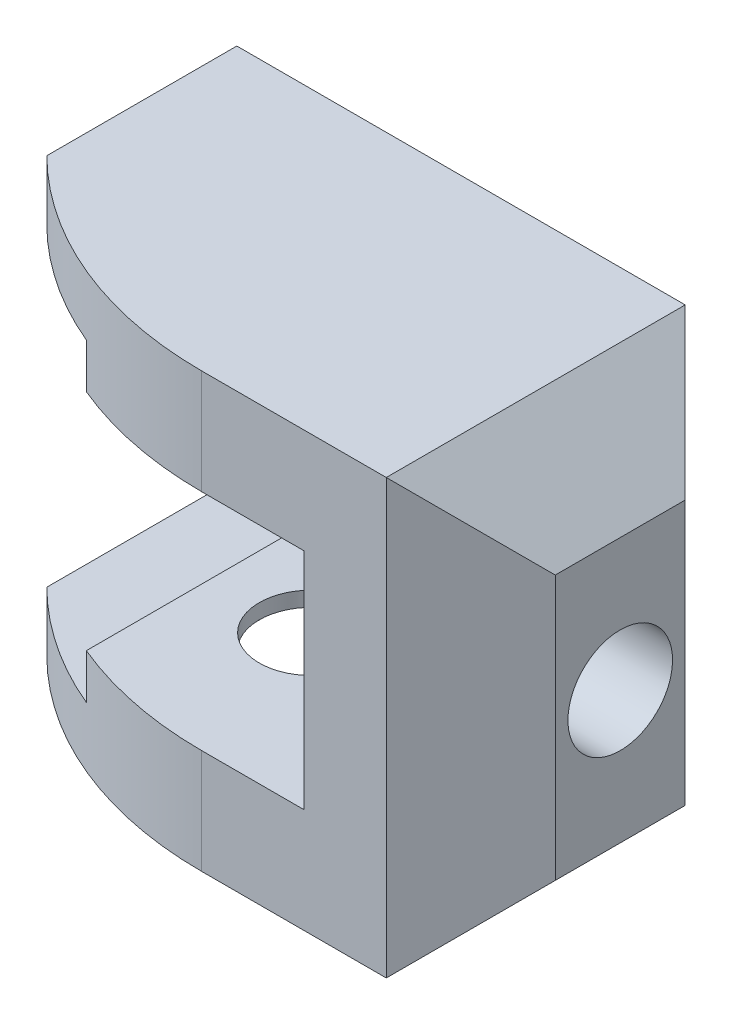
SolidWorks part; units mm, degrees
material "1060 Alloy"
ref_plane "Front Plane" through (0, 0, 0) normal (0, 0, 1) x (1, 0, 0)
ref_plane "Top Plane" through (0, 0, 0) normal (0, 1, 0) x (1, 0, 0)
ref_plane "Right Plane" through (0, 0, 0) normal (1, 0, 0) x (0, 0, -1)
sketch "Sketch2" plane through (0, 0, 0) normal (0, 0, 1) x (1, 0, 0)
  line L0 (60, 58) -> (71.3057, 46.6943)
  line L1 (0, 0) -> (60, 0)
  line L3 (0, 58) -> (60, 58)
  line L5 (71.3057, 46.6943) -> (71.3057, 11.3057)
  line L6 (71.3057, 11.3057) -> (60, 0)
  line L7 (0, 58) -> (0, 50)
  line L8 (0, 50) -> (16, 50)
  line L9 (16, 50) -> (16, 44)
  line L10 (16, 44) -> (45.9742, 44)
  line L11 (45.9742, 44) -> (49, 44)
  line L12 (49, 44) -> (49, 14)
  line L13 (49, 14) -> (16, 14)
  line L14 (16, 14) -> (16, 8)
  line L15 (16, 8) -> (0, 8)
  line L16 (0, 8) -> (0, 0)
  dimension "D1" = 45
  dimension "D2" = 45
  dimension "D3" = 8
  dimension "D4" = 6
  dimension "D5" = 8
  dimension "D6" = 6
  dimension "D7" = 16
  dimension "D8" = 16
  dimension "D9" = 11
  dimension "D10" = 11
  dimension "D11" = 58
  dimension "D12" = 60
extrude "Boss-Extrude1" add sketch "Sketch2" along normal blind 40
sketch "Sketch4" plane through (0, 0, 0) normal (0, -1, 0) x (1, 0, 0)
  line L0 (0, 40) -> (0, 0) construction
  line L1 (0, 40) -> (60, 40) construction
  line L2 (0, 25.4269) -> (0, 40)
  line L3 (0, 40) -> (35.2836, 40)
  arc A0 (0, 25.4269) -> (35.2836, 40) centre (35.2836, -10) cw
  dimension "D1" = 50
extrude "Cut-Extrude2" cut sketch "Sketch4" against normal through all
sketch "Sketch12" plane through (0, 0, 0) normal (0, 1, 0) x (1, 0, 0)
  line L0 (60, 0) -> (71.3057, -11.3057)
  line L1 (71.3057, 0) -> (60, 0) construction
  line L2 (60, -40) -> (60, 0) construction
  line L3 (71.3057, -40) -> (71.3057, 0) construction
  line L4 (71.3057, -11.3057) -> (71.3057, 0)
  line L5 (71.3057, 0) -> (60, 0)
  line L6 (60, -40) -> (71.3057, -28.6943)
  line L7 (71.3057, -28.6943) -> (71.3057, -40)
  line L8 (71.3057, -40) -> (60, -40)
  dimension "D1" = 45
  dimension "D2" = 45
extrude "Cut-Extrude3" cut sketch "Sketch12" along normal through all
sketch "Sketch14" plane through (71.3057, 0, 0) normal (1, 0, 0) x (0, 0, -1)
  circle A0 centre (-20, 29) radius 7
  dimension "D1" = 14
extrude "Cut-Extrude4" cut sketch "Sketch14" against normal through all
sketch "Sketch15" plane through (0, 0, 0) normal (0, -1, 0) x (1, 0, 0)
  circle A0 centre (29, 19) radius 7
  dimension "D1" = 14
extrude "Cut-Extrude5" cut sketch "Sketch15" against normal up to next
sketch "Sketch16" plane through (0, 44, 0) normal (0, -1, 0) x (1, 0, 0)
  circle A0 centre (29, 19) radius 7
extrude "Cut-Extrude6" cut sketch "Sketch16" against normal blind 2
sketch "Sketch21" plane through (0, 0, 0) normal (0, -1, 0) x (1, 0, 0)
  line L8 (0, 25.4269) -> (0, 0) construction
  line L9 (0, 22.5433) -> (0, 2)
  line L12 (58, 38) -> (35.2836, 38)
  line L13 (2, 24.5861) -> (2, 2)
  line L14 (2, 2) -> (58, 2)
  line L15 (58, 2) -> (58, 38)
  line L16 (58, 38) -> (35.2836, 38)
  line L18 (0, 2) -> (58, 2)
  line L19 (58, 2) -> (58, 38)
  arc A3 (35.2836, 38) -> (2, 24.5861) centre (35.2836, -10) ccw
  arc A4 (35.2836, 38) -> (0, 22.5433) centre (35.2836, -10) ccw
  dimension "D1" = 2
extrude "Cut-Extrude9" cut sketch "Sketch21" against normal blind 6
sketch "Sketch22" plane through (0, 6, 0) normal (0, -1, 0) x (1, 0, 0)
  line L0 (0, 2) -> (58, 2) construction
  line L1 (58, 2) -> (16.0233, 2)
  line L2 (58, 2) -> (58, 33.9663)
  line L3 (58, 33.9663) -> (16.0233, 33.9663)
  line L4 (16.0233, 2) -> (16.0233, 33.9663)
  arc A0 (35.2836, 38) -> (0, 22.5433) centre (35.2836, -10) ccw construction
extrude "Cut-Extrude11" cut sketch "Sketch22" against normal blind 6
sketch "Sketch23" plane through (0, 6, 0) normal (0, -1, 0) x (1, 0, 0)
  line L0 (16.0233, 33.9663) -> (58, 33.9663)
  line L1 (58, 33.9663) -> (58, 38)
  line L2 (58, 38) -> (34.0321, 37.9837)
  arc A0 (16.0233, 33.9663) -> (34.0321, 37.9837) centre (34.061, -4.5192) cw
  arc A1 (35.2836, 38) -> (16.0233, 33.9663) centre (35.2836, -10) ccw construction
extrude "Cut-Extrude12" cut sketch "Sketch23" against normal blind 6
equation "\"A\"= 58.00"
equation "\"B\"= 40.00"
equation "\"C\"= 60.00"
equation "\"D11@Sketch2\"=\"A\" "
equation "\"D12@Sketch2\"=\"C\" "
equation "\"D1@Boss-Extrude1\"=\"B\" "
